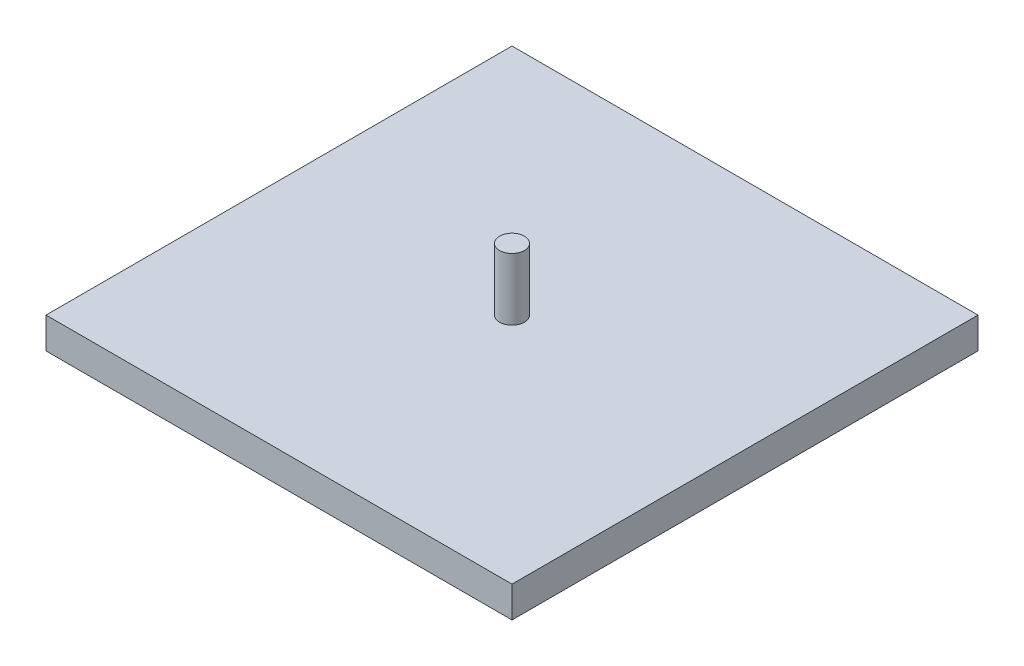
SolidWorks part; units mm, degrees
ref_plane "Front Plane" through (0, 0, 0) normal (0, 0, 1) x (1, 0, 0)
ref_plane "Top Plane" through (0, 0, 0) normal (0, 1, 0) x (1, 0, 0)
ref_plane "Right Plane" through (0, 0, 0) normal (1, 0, 0) x (0, 0, -1)
sketch "Sketch1" plane through (0, 0, 0) normal (0, 1, 0) x (1, 0, 0)
  line L1 (-36.9816, 28.5962) -> (113.0184, 28.5962)
  line L2 (-36.9816, 28.5962) -> (-36.9816, -121.4038)
  line L3 (-36.9816, -121.4038) -> (113.0184, -121.4038)
  line L4 (113.0184, 28.5962) -> (113.0184, -121.4038)
  dimension "D1" = 150
  dimension "D2" = 150
extrude "Boss-Extrude1" add sketch "Sketch1" along normal blind 10
sketch "Sketch4" plane through (0, 10, 0) normal (0, 1, 0) x (1, 0, 0)
  circle A0 centre (38.0184, -46.4038) radius 4
  dimension "D1" = 8
extrude "Boss-Extrude3" add sketch "Sketch4" along normal blind 20
